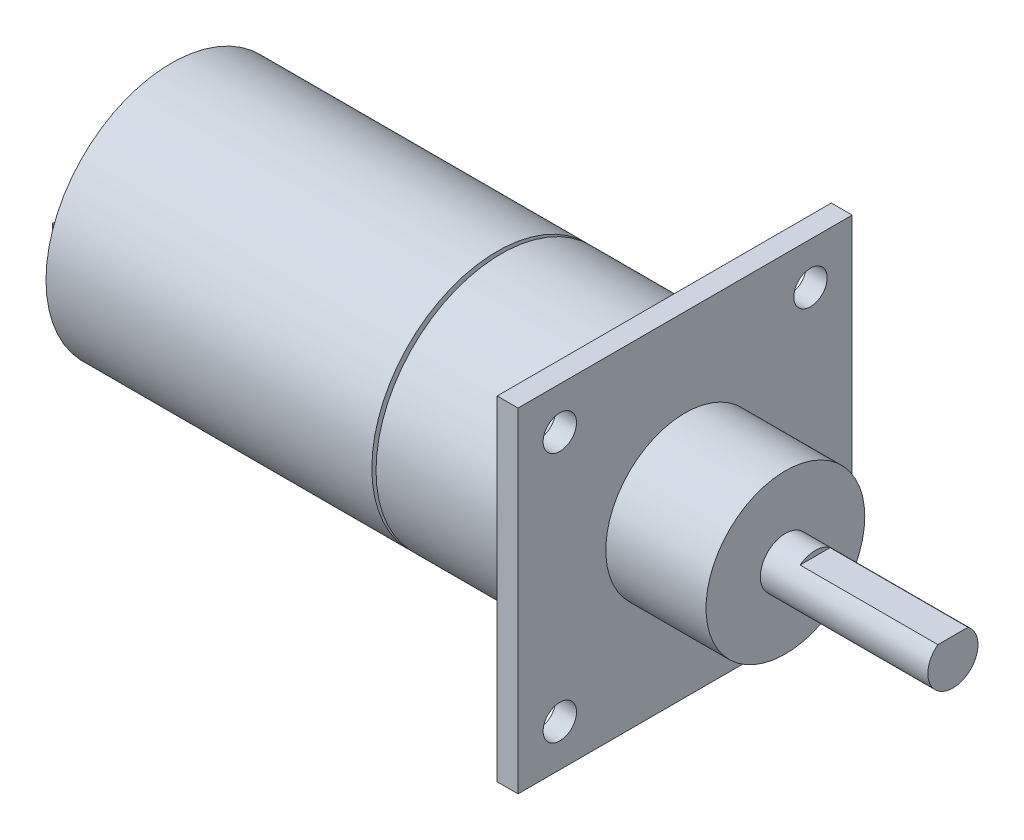
SolidWorks part; units mm, degrees
ref_plane "Alzado" through (0, 0, 0) normal (0, 0, 1) x (1, 0, 0)
ref_plane "Planta" through (0, 0, 0) normal (0, 1, 0) x (1, 0, 0)
ref_plane "Vista lateral" through (0, 0, 0) normal (1, 0, 0) x (0, 0, -1)
sketch "Croquis1" plane through (0, 0, 0) normal (0, 0, 1) x (1, 0, 0)
  line L0 (0, 0) -> (-93.5528, 0)
  line L1 (0, 0) -> (0, 3)
  line L2 (0, 3) -> (-20.0528, 3)
  line L3 (-20.0528, 3) -> (-20.0528, 9.5)
  line L4 (-20.0528, 9.5) -> (-32.0528, 9.5)
  line L5 (-32.0528, 9.5) -> (-32.0528, 15)
  line L6 (-32.0528, 15) -> (-54.0528, 15)
  line L7 (-54.0528, 15) -> (-54.0528, 14)
  line L8 (-54.0528, 14) -> (-54.5528, 14)
  line L9 (-54.5528, 14) -> (-54.5528, 15)
  line L10 (-54.5528, 15) -> (-93.5528, 15)
  line L11 (-93.5528, 15) -> (-93.5528, 4)
  line L12 (-93.5528, 4) -> (-96.5528, 4)
  line L13 (-96.5528, 4) -> (-96.5528, 1)
  line L14 (-96.5528, 1) -> (-98.5528, 1)
  line L15 (-98.5528, 1) -> (-98.5528, 0)
  line L16 (-98.5528, 0) -> (-93.5528, 0)
  dimension "D1" = 0.5
  dimension "D2" = 3
  dimension "D3" = 20.0528
  dimension "D4" = 12
  dimension "D5" = 22
  dimension "D6" = 39
  dimension "D7" = 5.5
  dimension "D8" = 6.5
  dimension "D9" = 3
  dimension "D10" = 1
  dimension "D11" = 3
  dimension "D12" = 1
  dimension "D13" = 2
revolve "Revolución1" add sketch "Croquis1" angle 360 about L0
sketch "Croquis2" plane through (-32.0528, 0, 0) normal (1, 0, 0) x (0, 0, -1)
  line L1 (-20, -20) -> (20, -20)
  line L2 (-20, -20) -> (-20, 20)
  line L3 (-20, 20) -> (20, 20)
  line L4 (20, -20) -> (20, 20)
  line L5 (-20, -20) -> (20, 20) construction
  line L6 (-20, 20) -> (20, -20) construction
  point P0 (0, 0)
extrude "Saliente-Extruir1" add sketch "Croquis2" against normal blind 2.5
sketch "Croquis3" plane through (-32.0528, 0, 0) normal (1, 0, 0) x (0, 0, -1)
  line L1 (-15, -15) -> (15, -15)
  line L2 (-15, -15) -> (-15, 15)
  line L3 (-15, 15) -> (15, 15)
  line L4 (15, -15) -> (15, 15)
  line L5 (-15, -15) -> (15, 15) construction
  line L6 (-15, 15) -> (15, -15) construction
  circle A0 centre (-15, 15) radius 2
  circle A1 centre (15, 15) radius 2
  circle A2 centre (-15, -15) radius 2
  circle A3 centre (15, -15) radius 2
  point P0 (0, 0)
extrude "Cortar-Extruir1" cut sketch "Croquis3" against normal blind 2.5 contours A2 | A0 | A1 | A3
sketch "Croquis6" plane through (0, 0, 0) normal (1, 0, 0) x (0, 0, -1)
  line L0 (0, -3) -> (0, 2.4)
  line L1 (-1.8, 2.4) -> (1.8, 2.4)
  circle A0 centre (0, 0) radius 3
  circle M1 centre (0, 0) radius 3
extrude "Cortar-Extruir2" cut sketch "Croquis6" against normal blind 16.5 contours L1 M1
sketch "Croquis7" plane through (-93.5528, 0, 0) normal (-1, 0, 0) x (0, 0, 1)
  line L1 (-10.25, -1.5) -> (-9.75, -1.5)
  line L2 (-10.25, -1.5) -> (-10.25, 1.5)
  line L3 (-10.25, 1.5) -> (-9.75, 1.5)
  line L4 (-9.75, -1.5) -> (-9.75, 1.5)
  line L5 (-10.25, -1.5) -> (-9.75, 1.5) construction
  line L6 (-10.25, 1.5) -> (-9.75, -1.5) construction
  line L7 (10.25, -1.5) -> (9.75, -1.5)
  line L8 (10.25, -1.5) -> (10.25, 1.5)
  line L9 (10.25, 1.5) -> (9.75, 1.5)
  line L10 (9.75, -1.5) -> (9.75, 1.5)
  line L11 (10.25, -1.5) -> (9.75, 1.5) construction
  line L12 (10.25, 1.5) -> (9.75, -1.5) construction
  point P0 (-10, 0)
  point P5 (10, 0)
  dimension "D1" = 10
  dimension "D2" = 10
extrude "Saliente-Extruir2" add sketch "Croquis7" along normal blind 4
